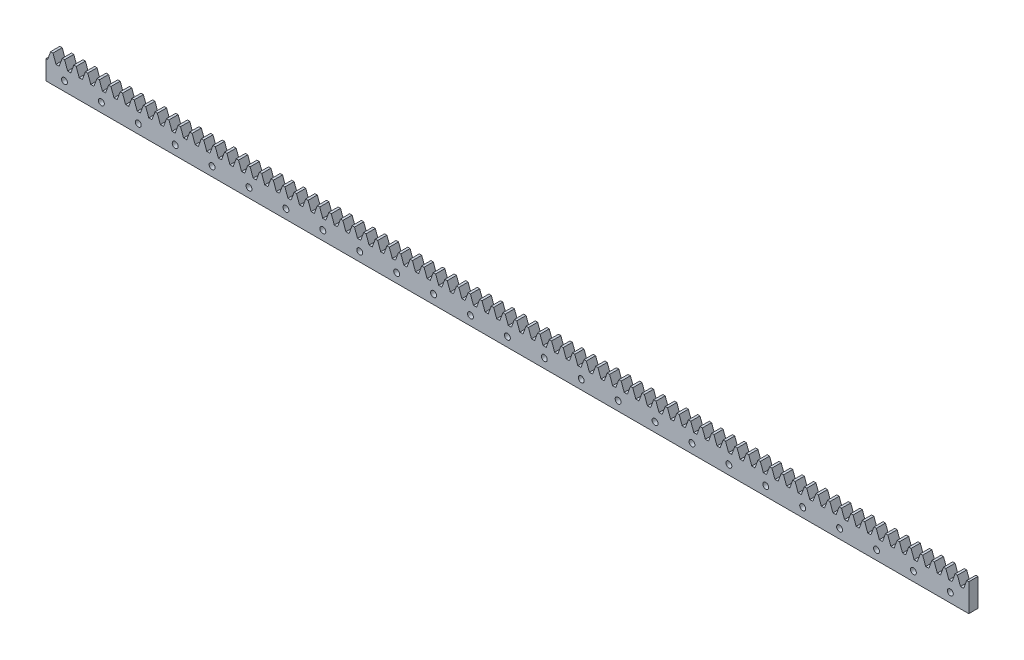
SolidWorks part; units mm, degrees
extrude "Blank" add sketch "BlankSke" against normal blind 5
sketch "BlankSke" plane through (0, 0, 0) normal (0, 0, 1) x (1, 0, 0)
  line L1 (0, 0) -> (500, 0)
  line L2 (0, 0) -> (0, 12)
  line L3 (0, 12) -> (500, 12)
  line L4 (500, 0) -> (500, 12)
  dimension "Length" = 500
  dimension "Blank_height" = 12
ref_plane "Plane1" through (0, 0, 0) normal (0, 0, 1) x (1, 0, 0)
ref_plane "Plane2" through (0, 0, 0) normal (0, 1, 0) x (1, 0, 0)
ref_plane "Plane3" through (0, 0, 0) normal (1, 0, 0) x (0, 0, -1)
other "Configuration Table"
sketch "HoldingSke" plane through (0, 0, 0) normal (0, 1, 0) x (1, 0, 0)
  line L0 (0, 0) -> (0.0696, 0.4951)
  line L1 (-15, 0) -> (100, 0) construction
  line L2 (0, 0) -> (-2.1039, 2.3779)
  line L3 (0, 0) -> (-11.863, 4.5341)
  line L4 (0, 0) -> (1.351, 8.5297)
  line L5 (0, 0) -> (-23.7986, -8.8762)
  line L6 (0, 0) -> (-10.5278, -7.1032)
  line L9 (-71.009, 38.7566) -> (398.8373, 209.7667)
  line L10 (-76.2, 4.3779) -> (-66.2, 4.3779)
  line L11 (0, 0) -> (-5, 0)
  line L12 (-76.2, 101.6) -> (-76.133, 101.6)
  line L13 (24.9733, 27.94) -> (52.9518, 28.4284)
  line L14 (24.9733, 27.94) -> (24.9743, 27.94)
  line L15 (24.9733, 27.94) -> (100.4006, 29.5858)
  circle A0 centre (0, 0) radius 19.05
  circle A1 centre (0, 0) radius 5
  circle A2 centre (0, 0) radius 12.7
  dimension "MPH" = 10
  dimension "Diameter" = 38.1
  dimension "Num_teeth" = 81
  dimension "Pitch" = 0.5
  dimension "Show_teeth" = 998
  dimension "Thickness" = 12.7
  dimension "Ap" = 20
  dimension "Pitch_height" = 10
  dimension "Width" = 5
  dimension "Backlash" = 0.067
  dimension "Addendum_fac" = 1
  dimension "Dedendum_fac" = 1.25
  dimension "Clearance_fac" = 0.25
  dimension "Dedendum_add" = 0.001
  dimension "Length" = 500
  dimension "Module" = 2
sketch "TooCutSkeIll" plane through (0, 0, 0) normal (0, 0, 1) x (1, 0, 0)
  line L0 (-2.4806, 11.9474) -> (-0.9819, 7.8296)
  line L1 (-0.5111, 7.5) -> (0.5111, 7.5)
  line L2 (0.9819, 7.8296) -> (2.4806, 11.9474)
  line L3 (500, 12) -> (0, 12) construction
  line L4 (0, 0) -> (0, 64.897) construction
  line L5 (-13.208, 10) -> (12.954, 10) construction
  line L6 (0, 0) -> (500, 0) construction
  line L7 (1.7718, 10) -> (1.7718, 48.7463) construction
  line L8 (-1.7718, 10) -> (-1.7718, 48.7463) construction
  line L9 (2.5558, 12) -> (2.5558, 12.0254)
  line L10 (-2.5558, 12) -> (-2.5558, 12.0254)
  line L11 (-2.5558, 12.0254) -> (2.5558, 12.0254)
  arc A0 (0.5111, 7.5) -> (0.9819, 7.8296) centre (0.5111, 8.001) ccw
  arc A1 (-0.9819, 7.8296) -> (-0.5111, 7.5) centre (-0.5111, 8.001) ccw
  arc A2 (2.5558, 12) -> (2.4806, 11.9474) centre (2.5558, 11.92) ccw
  arc A3 (-2.4806, 11.9474) -> (-2.5558, 12) centre (-2.5558, 11.92) ccw
  dimension "Pitch_height" = 10
  dimension "Addendum_plus" = 2.0254
  dimension "Pressure_angle" = 20
  dimension "Gap_width" = 3.5436
  dimension "Dedendum" = 2.5
extrude "ToothCutIll" [suppressed] cut sketch "TooCutSkeIll" against normal through all
sketch "TooCutSkeSim" plane through (0, 0, 0) normal (0, 0, 1) x (1, 0, 0)
  line L0 (0.8619, 7.5) -> (-0.8619, 7.5)
  line L1 (2.509, 12.0254) -> (0.8619, 7.5)
  line L2 (0, 17.4625) -> (0, 53.467) construction
  line L3 (2.509, 12.0254) -> (-2.509, 12.0254)
  line L6 (-2.509, 12.0254) -> (-0.8619, 7.5)
  line L9 (-1.7718, 10) -> (1.7718, 10) construction
  line L10 (0, 0) -> (500, 0) construction
  line L11 (1.7718, 10) -> (1.7718, 53.467) construction
  line L12 (-1.7718, 10) -> (-1.7718, 53.467) construction
  dimension "Pitch_height" = 10
  dimension "Addendum_plus" = 2.0254
  dimension "Pressure_angle" = 20
  dimension "Gap_width" = 3.5436
  dimension "Dedendum" = 2.5
extrude "ToothCutSim" cut sketch "TooCutSkeSim" against normal through all
pattern_linear "TeethCuts" count 80 spacing 6.2832 along (1, 0, 0) of "ToothCutIll", "ToothCutSim"
sketch "草图1" plane through (0, 0, 0) normal (0, 0, 1) x (1, 0, 0)
  line L0 (-0.0002, 10) -> (500, 10) construction
  line L1 (500, 0) -> (500, 12) construction
  line L2 (500, 12) -> (498.8714, 12) construction
  line L4 (0, 0) -> (500, 0)
  line L5 (0, 0) -> (0, -10)
  line L6 (0, -10) -> (500, -10)
  line L7 (500, 0) -> (500, -10)
  dimension "D1" = 2
  dimension "D2" = 10
sketch "草图2" plane through (0, 0, 0) normal (0, 0, 1) x (1, 0, 0)
  line L0 (500, 0) -> (500, 12) construction
  line L1 (0, 0) -> (500, 0)
  line L2 (0, 0) -> (0, -3)
  line L3 (0, -3) -> (500, -3)
  line L4 (500, 0) -> (500, -3)
  dimension "D1" = 3
extrude "凸台-拉伸2" add sketch "草图2" against normal blind 5
sketch "草图3" plane through (0, 0, -5) normal (0, 0, -1) x (-1, 0, 0)
  line L0 (-500, -3) -> (-500, 7) construction
  line L1 (-500, -3) -> (-500, 12) construction
  line L2 (-500, 2) -> (-490, 2) construction
  circle A0 centre (-490, 2) radius 1.6
  circle A1 centre (-470, 2) radius 1.6
  circle A2 centre (-450, 2) radius 1.6
  circle A3 centre (-430, 2) radius 1.6
  circle A4 centre (-410, 2) radius 1.6
  circle A5 centre (-390, 2) radius 1.6
  circle A6 centre (-370, 2) radius 1.6
  circle A7 centre (-350, 2) radius 1.6
  circle A8 centre (-330, 2) radius 1.6
  circle A9 centre (-310, 2) radius 1.6
  circle A10 centre (-290, 2) radius 1.6
  circle A11 centre (-270, 2) radius 1.6
  circle A12 centre (-250, 2) radius 1.6
  circle A13 centre (-230, 2) radius 1.6
  circle A14 centre (-210, 2) radius 1.6
  circle A15 centre (-190, 2) radius 1.6
  circle A16 centre (-170, 2) radius 1.6
  circle A17 centre (-150, 2) radius 1.6
  circle A18 centre (-130, 2) radius 1.6
  circle A19 centre (-110, 2) radius 1.6
  circle A20 centre (-90, 2) radius 1.6
  circle A21 centre (-70, 2) radius 1.6
  circle A22 centre (-50, 2) radius 1.6
  circle A23 centre (-30, 2) radius 1.6
  circle A24 centre (-10, 2) radius 1.6
  dimension "D2" = 3.2
  dimension "D1" = 10
  dimension "D3" = 10
  dimension "D4" = 25
extrude "切除-拉伸1" cut sketch "草图3" against normal through all
equation "' \"Module@HoldingSke\" = 6.35"
equation "' \"Num_teeth@HoldingSke\" = 12"
equation "' \"Ap@HoldingSke\" =  20"
equation "' \"Ap@HoldingSke\" = 20"
equation "' \"Width@HoldingSke\" = 0.25 * 25.4"
equation "' \"Show_teeth@HoldingSke\" = 500"
equation "' \"Backlash@HoldingSke\" = 0.009 * 25.4"
equation "' \"Addendum_fac@HoldingSke\" = 1.0"
equation "' \"Dedendum_fac@HoldingSke\" = 1.25"
equation "' \"Dedendum_add@HoldingSke\" = 0.00005 * 25.4"
equation "' \"Clearance_fac@HoldingSke\" = 0.25"
equation "' \"Pitch_height@HoldingSke\" = 1 * 25.4"
equation "' \"Length@HoldingSke\" = 4.71 * 25.4"
equation "\"Pitch@HoldingSke\" = 1 / \"Module@HoldingSke\""
equation "\"MPH@HoldingSke\" = \"Dedendum_fac@HoldingSke\" / \"Pitch@HoldingSke\" + 2 * \"Dedendum_add@HoldingSke\" + 0.002 * 25.4"
equation "\"MPH@HoldingSke\" = ((sgn( \"MPH@HoldingSke\" - \"Pitch_height@HoldingSke\")+1)*( \"MPH@HoldingSke\" - \"Pitch_height@HoldingSke\"))/2 + \"Pitch_height@HoldingSke\""
equation "\"Blank_height@BlankSke\" = \"Pitch_height@HoldingSke\" + \"Addendum_fac@HoldingSke\"  / \"Pitch@HoldingSke\" "
equation "\"Length@BlankSke\" =  \"Length@HoldingSke\""
equation "\"Face_width@Blank\" = \"Width@HoldingSke\""
equation "\"Pressure_angle@TooCutSkeIll\" = \"Ap@HoldingSke\""
equation "\"Addendum_plus@TooCutSkeIll\" =  \"Addendum_fac@HoldingSke\"  / \"Pitch@HoldingSke\" + 0.001 *25.4"
equation "\"Dedendum@TooCutSkeIll\" = \"Dedendum_fac@HoldingSke\"  / \"Pitch@HoldingSke\""
equation "\"Pitch_height@TooCutSkeIll\" =  \"MPH@HoldingSke\""
equation "\"Gap_width@TooCutSkeIll\" = 3.14159265 / 2 / \"Pitch@HoldingSke\" + 6 * \"Backlash@HoldingSke\""
equation "\"Pressure_angle@TooCutSkeSim\" = \"Ap@HoldingSke\""
equation "\"Addendum_plus@TooCutSkeSim\" =  \"Addendum_fac@HoldingSke\"  / \"Pitch@HoldingSke\" + 0.001 * 25.4"
equation "\"Dedendum@TooCutSkeSim\" = \"Dedendum_fac@HoldingSke\"  / \"Pitch@HoldingSke\""
equation "\"Pitch_height@TooCutSkeSim\" =  \"MPH@HoldingSke\""
equation "\"Gap_width@TooCutSkeSim\" = 3.14159265 / 2 / \"Pitch@HoldingSke\" + 6 * \"Backlash@HoldingSke\""
equation "\"Root_fillet@TooCutSkeIll\" = \"Clearance_fac@HoldingSke\" / \"Pitch@HoldingSke\" + \"Dedendum_add@HoldingSke\""
equation "\"Break_rad@TooCutSkeIll\" = 0.02 / \"Pitch@HoldingSke\" * 2"
equation "\"Linear_pitch@TeethCuts\" = 3.14159265 / \"Pitch@HoldingSke\""
equation "\"Num_teeth@HoldingSke\" = int( ( \"Length@HoldingSke\" + 0 ) / (3.14159265 / \"Pitch@HoldingSke\")) + 0.9999  + 1"
equation " \"Num_teeth@TeethCuts\" = int( \"Show_teeth@HoldingSke\" ) + 1"
equation " \"Num_teeth@TeethCuts\" = ((sgn( \"Num_teeth@TeethCuts\" - \"Num_teeth@HoldingSke\" )-1)*( \"Num_teeth@TeethCuts\" - \"Num_teeth@HoldingSke\" ))/-2+ \"Num_teeth@HoldingSke\""
equation " \"Num_teeth@TeethCuts\" = ((sgn( \"Num_teeth@TeethCuts\" - 2.0)+1)*( \"Num_teeth@TeethCuts\" - 2.0))/2 +2.0"
